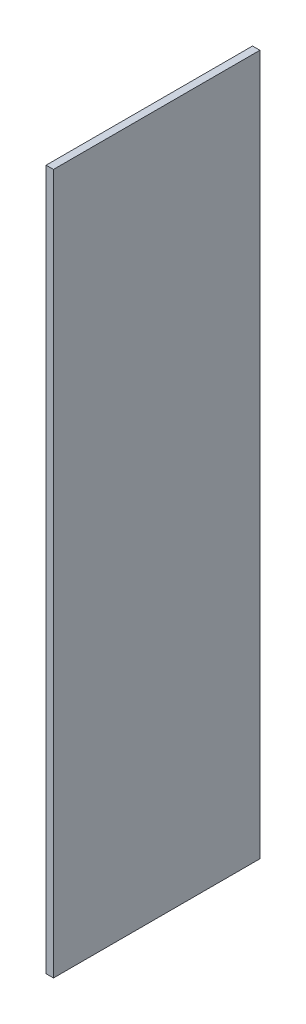
SolidWorks part; units mm, degrees
material "Custom Plastic"
ref_plane "Front Plane" through (0, 0, 0) normal (1, 0, 0) x (0, 1, 0)
ref_plane "Top Plane" through (0, 0, 0) normal (0, 0, 1) x (0, 1, 0)
ref_plane "Right Plane" through (0, 0, 0) normal (0, 1, 0) x (-1, 0, 0)
sketch "Sketch1" plane through (0, 0, 0) normal (1, 0, 0) x (0, 1, 0)
  line L1 (-475, 140) -> (475, 140)
  line L2 (-475, 140) -> (-475, -140)
  line L3 (-475, -140) -> (475, -140)
  line L4 (475, 140) -> (475, -140)
  line L5 (-475, 140) -> (475, -140) construction
  line L6 (-475, -140) -> (475, 140) construction
  point P0 (0, 0)
  dimension "D1" = 950
  dimension "D2" = 280
extrude "Boss-Extrude1" add sketch "Sketch1" along normal blind 10
